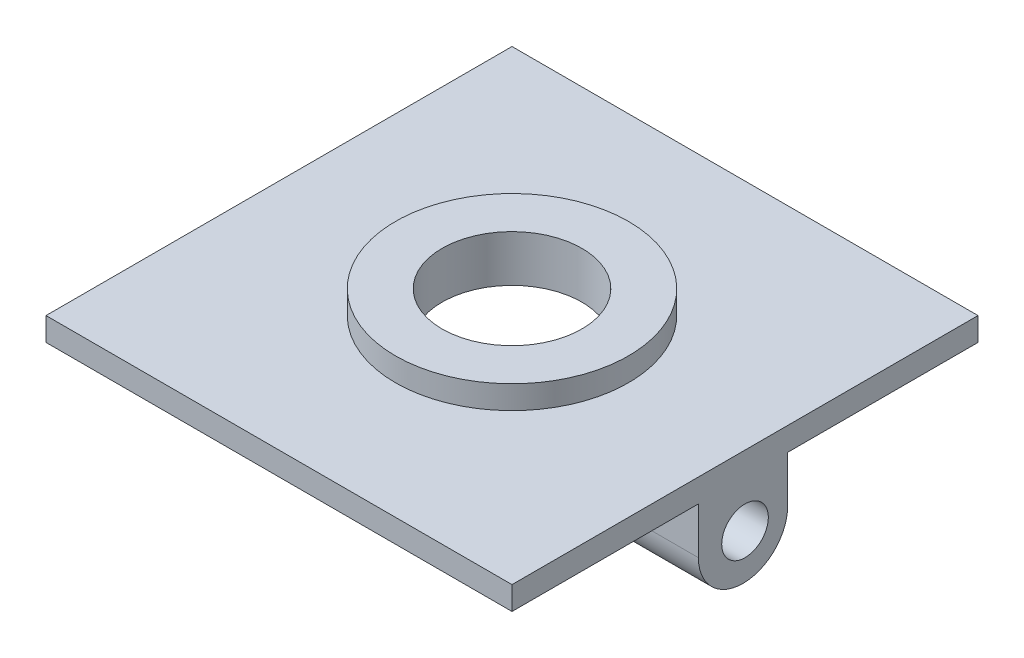
SolidWorks part; units mm, degrees
material "自定义塑料"
ref_plane "前视基准面" through (0, 0, 0) normal (0, 0, 1) x (1, 0, 0)
ref_plane "上视基准面" through (0, 0, 0) normal (0, 1, 0) x (1, 0, 0)
ref_plane "右视基准面" through (0, 0, 0) normal (1, 0, 0) x (0, 0, -1)
sketch "草图1" plane through (0, 0, 0) normal (0, 1, 0) x (1, 0, 0)
  line L1 (0, 0) -> (100, 0)
  line L2 (0, 0) -> (0, -100)
  line L3 (0, -100) -> (100, -100)
  line L4 (100, 0) -> (100, -100)
extrude "凸台-拉伸1" add sketch "草图1" along normal blind 5
sketch "草图2" plane through (0, 5, 0) normal (0, 1, 0) x (1, 0, 0)
  circle A0 centre (50, -50) radius 25
extrude "凸台-拉伸2" add sketch "草图2" along normal blind 5
sketch "草图3" plane through (0, 10, 0) normal (0, 1, 0) x (1, 0, 0)
  circle A0 centre (50, -50) radius 15
extrude "切除-拉伸1" cut sketch "草图3" against normal blind 10
sketch "草图4" plane through (100, 0, 0) normal (1, 0, 0) x (0, 0, -1)
  line L0 (-60, 0) -> (-40.8515, 0)
  line L1 (-100, 0) -> (0, 0) construction
  line L4 (-60, 0) -> (-60, -10)
  line L6 (-40.8515, 0) -> (-40.8515, -10)
  arc A0 (-60, -10) -> (-40.8515, -10) centre (-50.4258, -10) ccw
extrude "凸台-拉伸3" add sketch "草图4" against normal blind 20
sketch "草图5" plane through (0, 0, 0) normal (-1, 0, 0) x (0, 0, 1)
  line L1 (0, 0) -> (100, 0) construction
  line L3 (40, 0) -> (60, 0)
  line L4 (40, 0) -> (40, -10)
  line L6 (60, 0) -> (60, -10)
  arc A0 (40, -10) -> (60, -10) centre (50, -10) ccw
extrude "凸台-拉伸4" add sketch "草图5" against normal blind 20
sketch "草图6" plane through (0, 0, 0) normal (-1, 0, 0) x (0, 0, 1)
  circle A0 centre (50, -10) radius 5
extrude "切除-拉伸2" cut sketch "草图6" against normal blind 100
sketch "草图7" plane through (0, 0, 0) normal (0, -1, 0) x (1, 0, 0)
  line L0 (50, 100) -> (50, 65)
  line L1 (0, 100) -> (100, 100) construction
  circle A0 centre (50, 50) radius 15 construction
